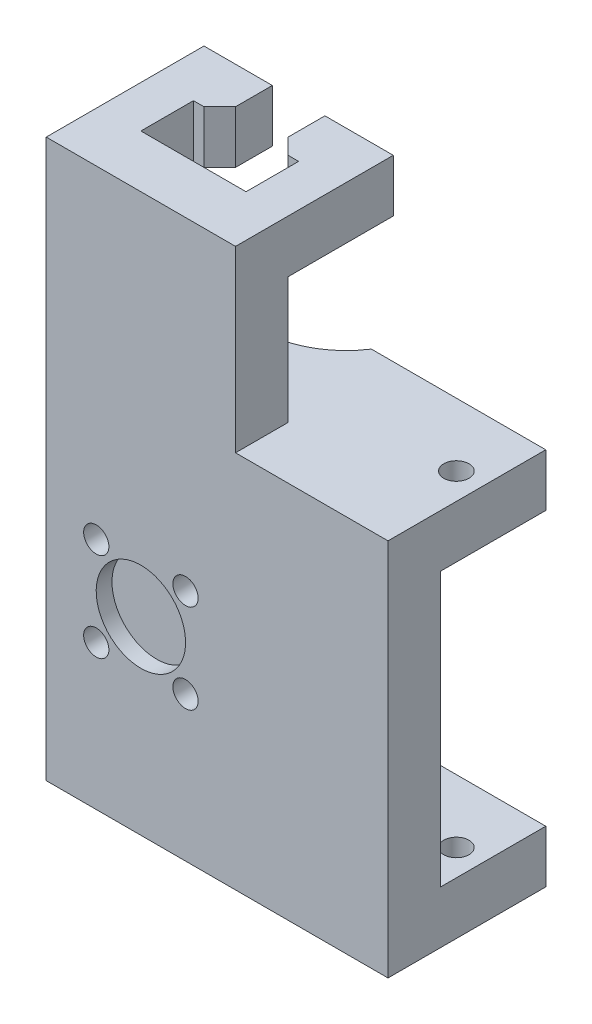
SolidWorks part; units mm, degrees
ref_plane "正面" through (0, 0, 0) normal (0, 0, 1) x (1, 0, 0)
ref_plane "平面" through (0, 0, 0) normal (0, 1, 0) x (1, 0, 0)
ref_plane "右側面" through (0, 0, 0) normal (1, 0, 0) x (0, 0, -1)
sketch "ｽｹｯﾁ1" plane through (0, 0, 0) normal (0, 0, 1) x (1, 0, 0)
  line L1 (-16.25, 18) -> (16.25, 18)
  line L2 (-16.25, 18) -> (-16.25, -18)
  line L3 (-16.25, -18) -> (16.25, -18)
  line L4 (16.25, 18) -> (16.25, -18)
  line L5 (-16.25, 18) -> (16.25, -18) construction
  line L6 (-16.25, -18) -> (16.25, 18) construction
  point P0 (0, 0)
  dimension "D1" = 36
  dimension "D2" = 32.5
extrude "ﾎﾞｽ - 押し出し1" add sketch "ｽｹｯﾁ1" along normal blind 15
sketch "ｽｹｯﾁ2" plane through (16.25, 0, 0) normal (1, 0, 0) x (0, 0, -1)
  line L0 (0, -18) -> (0, 18) construction
  line L1 (0, 13) -> (-10, 13)
  line L2 (0, 13) -> (0, -13)
  line L3 (0, -13) -> (-10, -13)
  line L4 (-10, 13) -> (-10, -13)
  line L5 (-15, -18) -> (-15, 18) construction
  point P6 (0, 0)
  point P8 (0, 0)
  dimension "D1" = 26
  dimension "D2" = 5
extrude "ｶｯﾄ - 押し出し1" cut sketch "ｽｹｯﾁ2" against normal through all
hole_wizard "M2 すきま穴1" positions "ｽｹｯﾁ5" profile "ｽｹｯﾁ6" hole size "M2" standard "JIS"
sketch "ｽｹｯﾁ5" plane through (0, 13, 0) normal (0, -1, 0) x (1, 0, 0)
  line L0 (-16.25, 10) -> (16.25, 10) construction
  line L1 (16.25, 0) -> (16.25, 10) construction
  point P0 (13.75, 6)
  point P2 (-7.25, 6)
  point P19 (0, 0)
  dimension "D1" = 4
  dimension "D2" = 2.5
  dimension "D3" = 23.5
sketch "ｽｹｯﾁ6" plane through (13.75, 13, 6) normal (1, 0, 0) x (0, 0, -1)
  line L0 (0, 0) -> (0, 5)
  line L1 (0, 5) -> (1.2, 5)
  line L2 (1.2, 5) -> (1.2, 0)
  line L5 (1.2, 0) -> (0, 0)
  line L11 (0, -6.35) -> (0, 107.95) construction
  dimension "通し穴の直径" = 2.4
  dimension "通し穴の深さ" = 5
sketch "ｽｹｯﾁ4" plane through (0, 13, 0) normal (0, -1, 0) x (1, 0, 0)
  circle A0 centre (-7.25, -4.5) radius 8.25
  circle A2 centre (-7.25, 6) radius 1.2 construction
  circle A3 centre (-7.25, 6) radius 1.2
  point P4 (0, 0)
  dimension "D1" = 16.5
  dimension "D2" = 10.5
extrude "ｶｯﾄ - 押し出し3" cut sketch "ｽｹｯﾁ4" against normal through all both and the other way through all
mirror "ﾐﾗｰ1" about plane through (0, 0, 0) normal (0, 1, 0) of "M2 すきま穴1"
hole_wizard "M2 丸平ねじ用座ぐり穴2" positions "ｽｹｯﾁ11" profile "ｽｹｯﾁ12" counterbore size "M2" standard "JIS" end condition through all
sketch "ｽｹｯﾁ11" plane through (0, 0, 10) normal (0, 0, -1) x (-1, 0, 0)
  line L1 (11.4926, 4.2426) -> (3.0074, 4.2426)
  line L2 (11.4926, 4.2426) -> (11.4926, -4.2426)
  line L3 (11.4926, -4.2426) -> (3.0074, -4.2426)
  line L4 (3.0074, 4.2426) -> (3.0074, -4.2426)
  line L5 (-16.25, 13) -> (-16.25, -13) construction
  point P2 (11.4926, 4.2426)
  point P3 (3.0074, -4.2426)
  point P196 (11.4926, -4.2426)
  point P197 (3.0074, 4.2426)
  point P199 (3.0074, 0)
  point P210 (7.25, 4.2426)
  dimension "D1" = 12
  dimension "D2" = 23.5
sketch "ｽｹｯﾁ12" plane through (-11.4926, 4.2426, 10) normal (1, 0, 0) x (0, 1, 0)
  line L0 (0, 0) -> (0, 5)
  line L1 (0, 5) -> (1.2, 5)
  line L3 (1.2, 5) -> (1.2, 1.45)
  line L4 (1.2, 1.45) -> (1.925, 1.45)
  line L5 (1.925, 1.45) -> (1.925, 0)
  line L7 (1.925, 0) -> (0, 0)
  line L11 (0, -6.35) -> (0, 107.95) construction
  dimension "通し穴の直径" = 2.4
  dimension "通し穴の深さ" = 5
  dimension "座ぐり穴の直径" = 3.85
  dimension "座ぐり穴の深さ" = 1.45
sketch "ｽｹｯﾁ13" plane through (0, 18, 0) normal (0, 1, 0) x (1, 0, 0)
  line L0 (16.25, 0) -> (-0.3353, 0) construction
  line L1 (-16.25, -15) -> (1.75, -15)
  line L2 (-16.25, -15) -> (-16.25, 0)
  line L3 (-16.25, 0) -> (1.75, 0)
  line L4 (1.75, -15) -> (1.75, 0)
  point P7 (-7.25, -6)
  point P8 (0, 0)
  point P10 (-7.25, -15)
extrude "ﾎﾞｽ - 押し出し3" add sketch "ｽｹｯﾁ13" along normal blind 17
sketch "ｽｹｯﾁ14" plane through (0, 0, 0) normal (0, 0, -1) x (-1, 0, 0)
  line L0 (16.25, 35) -> (16.25, 13) construction
  line L1 (-1.75, 18) -> (16.25, 18)
  line L2 (-1.75, 18) -> (-1.75, 30)
  line L3 (-1.75, 30) -> (16.25, 30)
  line L4 (16.25, 18) -> (16.25, 30)
  line L5 (-1.75, 35) -> (16.25, 35) construction
  dimension "D1" = 5
extrude "ｶｯﾄ - 押し出し4" cut sketch "ｽｹｯﾁ14" against normal blind 10 and the other way through all
sketch "ｽｹｯﾁ15" plane through (0, 35, 0) normal (0, 1, 0) x (1, 0, 0)
  line L0 (1.75, 0) -> (-16.25, 0) construction
  line L1 (-4.75, 0) -> (-9.75, 0)
  line L2 (-4.75, 0) -> (-4.75, -10)
  line L3 (-4.75, -10) -> (-9.75, -10)
  line L4 (-9.75, 0) -> (-9.75, -10)
  point P6 (-7.25, 0)
  point P7 (-7.25, 0)
  dimension "D1" = 5
  dimension "D2" = 10
extrude "ｶｯﾄ - 押し出し5" cut sketch "ｽｹｯﾁ15" against normal up to next
sketch "ｽｹｯﾁ16" plane through (0, 35, 0) normal (0, 1, 0) x (1, 0, 0)
  line L0 (-16.25, -15) -> (1.75, -15) construction
  line L1 (-2.25, -5) -> (-12.25, -5)
  line L2 (-2.25, -5) -> (-2.25, -10)
  line L3 (-2.25, -10) -> (-12.25, -10)
  line L4 (-12.25, -5) -> (-12.25, -10)
  line L5 (-9.75, 0) -> (-16.25, 0) construction
  point P7 (-7.25, -15)
  point P8 (-7.25, -10)
  dimension "D1" = 10
  dimension "D2" = 5
extrude "ｶｯﾄ - 押し出し6" cut sketch "ｽｹｯﾁ16" against normal up to next
chamfer "面取り1" distance 1.5 angle 45 2 edges at (-9.75, 32.5, 5) (-4.75, 32.5, 5)
sketch "ｽｹｯﾁ17" plane through (0, 0, 15) normal (0, 0, 1) x (1, 0, 0)
  line L0 (-11.4926, 4.2426) -> (-3.0074, 4.2426)
  line L1 (-3.0074, 4.2426) -> (-3.0074, -4.2426)
  circle A0 centre (-7.25, 0) radius 4.25
  point P6 (-7.25, 4.2426)
  point P9 (-3.0074, 0)
  dimension "D1" = 8.5
extrude "ｶｯﾄ - 押し出し7" cut sketch "ｽｹｯﾁ17" against normal blind 1.5 contours L1 A0 L0
